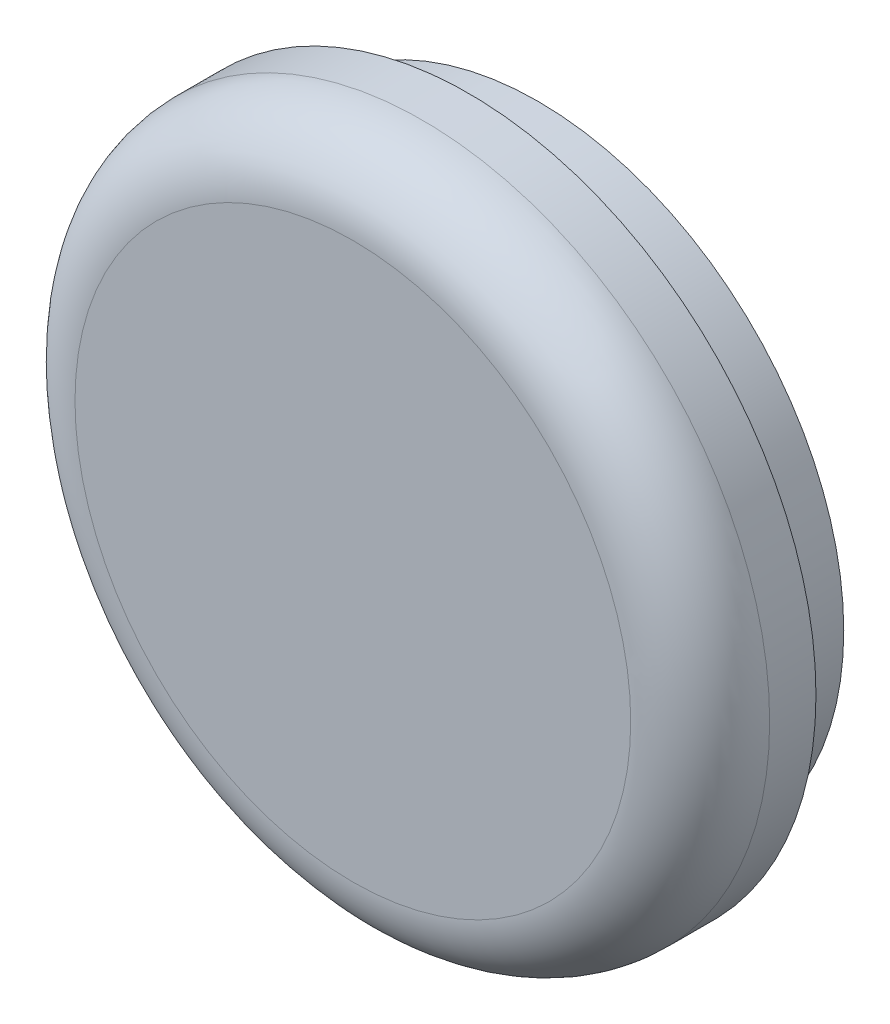
SolidWorks part; units mm, degrees
ref_plane "Front Plane" through (0, 0, 0) normal (0, 0, 1) x (1, 0, 0)
ref_plane "Top Plane" through (0, 0, 0) normal (0, 1, 0) x (1, 0, 0)
ref_plane "Right Plane" through (0, 0, 0) normal (1, 0, 0) x (0, 0, -1)
sketch "Sketch1" plane through (0, 0, 0) normal (0, 0, 1) x (1, 0, 0)
  circle A0 centre (0, 0) radius 15
extrude "Boss-Extrude1" add sketch "Sketch1" along normal blind 5
fillet "Fillet1" radius 3 1 edges at (15, 0, 5)
sketch "Sketch2" plane through (0, 0, 0) normal (0, 0, -1) x (-1, 0, 0)
  circle A0 centre (0, 0) radius 12
extrude "Cut-Extrude1" cut sketch "Sketch2" against normal blind 3.5 contours A0
fillet "Fillet2" radius 3 1 edges at (-12, 0, 3.5)
sketch "Sketch4" plane through (0, 0, 0) normal (0, 0, -1) x (-1, 0, 0)
  circle A0 centre (0, 0) radius 13.2
extrude "Boss-Extrude3" add sketch "Sketch4" along normal blind 3
sketch "Sketch5" plane through (0, 0, -3) normal (0, 0, -1) x (-1, 0, 0)
  circle A0 centre (0, 0) radius 12
extrude "Cut-Extrude2" cut sketch "Sketch5" against normal blind 3
